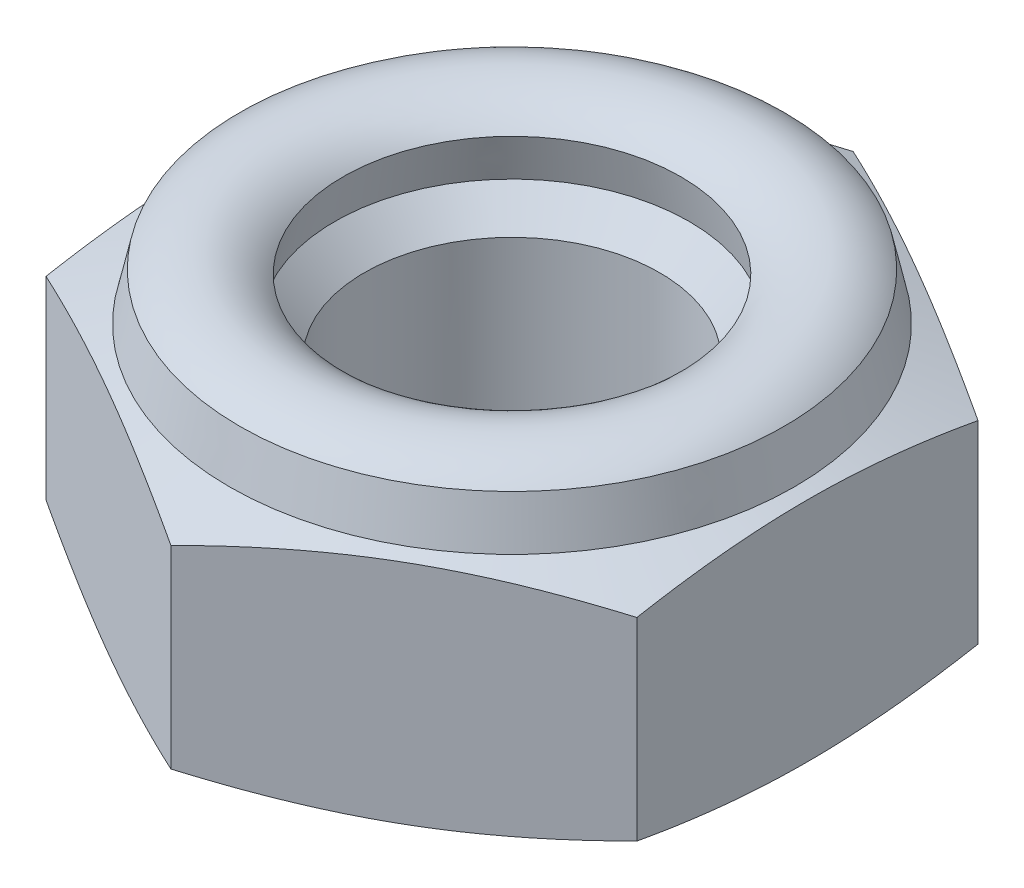
SolidWorks part; units mm, degrees
material "普通碳钢"
ref_plane "前视" through (0, 0, 0) normal (0, 0, 1) x (1, 0, 0)
ref_plane "上视" through (0, 0, 0) normal (0, 1, 0) x (1, 0, 0)
ref_plane "右视" through (0, 0, 0) normal (1, 0, 0) x (0, 0, -1)
sketch "草图1" plane through (0, 0, 0) normal (0, 1, 0) x (1, 0, 0)
  line L0 (0, 3.1049) -> (0, -3.4641) construction
  line L1 (0, -2.3094) -> (2, -1.1547)
  line L2 (2, -1.1547) -> (2, 1.1547)
  line L3 (2, 1.1547) -> (0, 2.3094)
  line L4 (0, 2.3094) -> (-2, 1.1547)
  line L5 (-2, 1.1547) -> (-2, -1.1547)
  line L6 (-2, -1.1547) -> (0, -2.3094)
  circle A0 centre (0, 0) radius 2 construction
  dimension "D1" = 4
extrude "拉伸1" add sketch "草图1" along normal blind 1.6
hole_wizard "M2 螺纹孔1" positions "草图3" profile "草图2" tap size "M2" standard "DIN"
sketch "草图3" plane through (0, 1.6, 0) normal (0, 1, 0) x (-1, 0, 0)
  point P0 (0, 0)
sketch "草图2" plane through (0, 1.6, 0) normal (1, 0, 0) x (0, 0, 1)
  line L0 (0, 0) -> (0, 6.4807)
  line L1 (0, 6.4807) -> (0.8, 6)
  line L2 (0.8, 6) -> (0.8, 4)
  line L3 (0.8, 4) -> (1, 4)
  line L4 (1, 4) -> (1, 0)
  line L5 (1, 0) -> (0, 0)
  line L10 (0, 6.4807) -> (-0.8, 6) construction
  line L11 (0, -6.35) -> (0, 107.95) construction
  dimension "蹟恇謂郰芛眻噤" = 1.6
  dimension "蹟恇謂郰芛旮僅" = 6
  dimension "蹟恇翋眻噤" = 2
  dimension "蹟恇旮僅" = 4
  dimension "絳芛褒僅" = 118
sketch "草图4" plane through (0, 0, 0) normal (1, 0, 0) x (0, 0, -1)
  line L0 (1.9124, 0) -> (2.3094, 0.1445)
  line L1 (0, 3.0267) -> (0, -1.2162) construction
  line L3 (2.3094, 1.6) -> (2.3094, 1.4555)
  line L4 (-2.3094, 0.8) -> (2.3094, 0.8) construction
  line L5 (-2.3094, 1.6) -> (-1.1547, 1.6) construction
  line L6 (1.9124, 0) -> (2.3094, 0)
  line L7 (1.9124, 1.6) -> (2.3094, 1.6)
  line L8 (1.9124, 1.6) -> (2.3094, 1.4555)
  line L9 (2.3094, 0) -> (2.3094, 0.1445)
  line L10 (-2.3094, 1.6) -> (-2.3094, 0) construction
  line L12 (2.3094, 1.6) -> (2.3094, 0) construction
  line L13 (1.1547, 1.6) -> (2.3094, 1.6) construction
  dimension "D1" = 20
revolve "切除-旋转2" cut sketch "草图4" angle 360 about L1
chamfer "倒角1" distance 0.2 angle 45 2 edges at (0, 1.6, 1) (0, 0, -1)
sketch "草图5" plane through (0, 0, 0) normal (0, 0, 1) x (1, 0, 0)
  line L0 (1.9124, 1.6) -> (-1.9124, 1.6) construction
  line L2 (1.9124, 1.6) -> (1.2, 1.6)
  line L3 (1.2, 1.6) -> (1.1434, 1.8908)
  line L4 (0, 0) -> (0, 2.2735) construction
  line L5 (1.9124, 1.6) -> (1.8417, 1.9188)
  arc A0 (1.1434, 1.8908) -> (1.8417, 1.9188) centre (1.5078, 1.524) cw
revolve "旋转1" add sketch "草图5" angle 360 about L4
